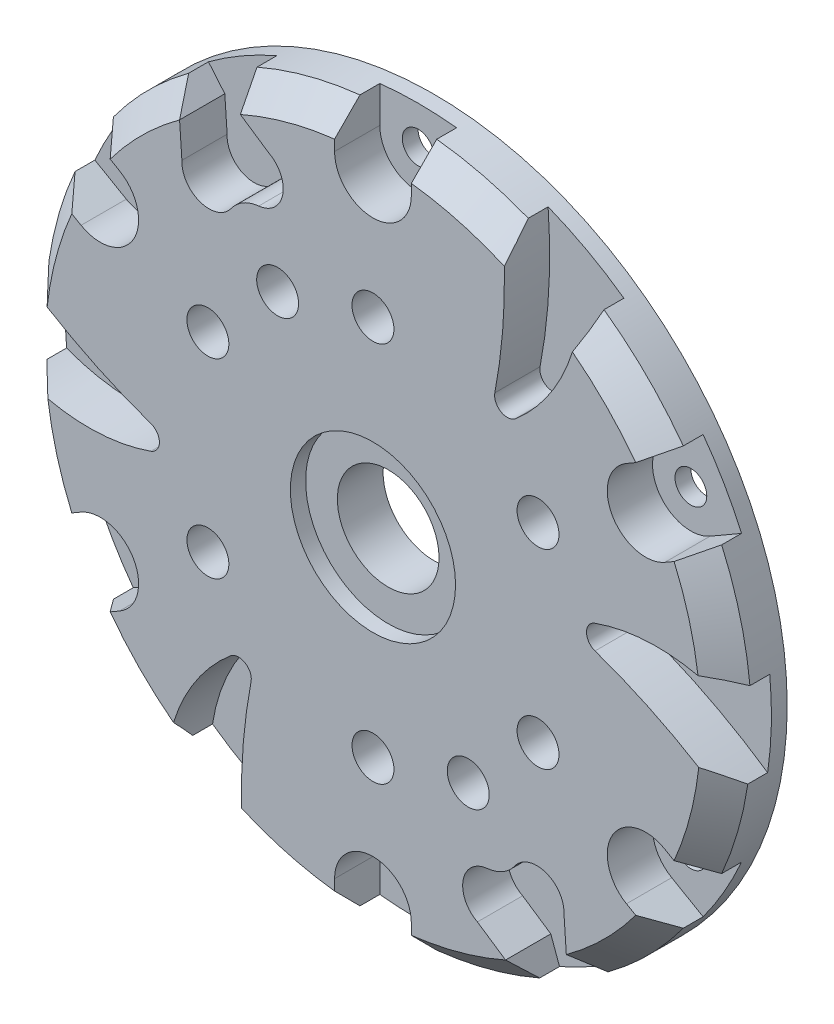
SolidWorks part; units mm, degrees
ref_plane "Front Plane" through (0, 0, 0) normal (0, 0, 1) x (1, 0, 0)
ref_plane "Top Plane" through (0, 0, 0) normal (0, 1, 0) x (1, 0, 0)
ref_plane "Right Plane" through (0, 0, 0) normal (1, 0, 0) x (0, 0, -1)
sketch "Sketch1" plane through (0, 0, 0) normal (0, 0, 1) x (1, 0, 0)
  circle A0 centre (0, 0) radius 27.8
  dimension "D1" = 55.6
extrude "Boss-Extrude1" add sketch "Sketch1" along normal blind 4.8
chamfer "Chamfer1" distance 2 angle 45 1 edges at (27.8, 0, 4.8)
sketch "Sketch2" plane through (0, 0, 4.8) normal (0, 0, 1) x (1, 0, 0)
  line L0 (0, 0) -> (0, 27.8) construction
  line L1 (-3.02, 24.78) -> (-3.02, 27.6355)
  line L2 (3.02, 24.78) -> (3.02, 27.6355)
  line L3 (19.9501, 15.0054) -> (22.423, 16.4331)
  line L4 (22.9701, 9.7746) -> (25.443, 11.2023)
  line L5 (0, 0) -> (24.0755, 13.9) construction
  line L6 (22.9701, -9.7746) -> (25.443, -11.2023)
  line L7 (19.9501, -15.0054) -> (22.423, -16.4331)
  line L8 (0, 0) -> (24.0755, -13.9) construction
  line L9 (3.02, -24.78) -> (3.02, -27.6355)
  line L10 (-3.02, -24.78) -> (-3.02, -27.6355)
  line L11 (0, 0) -> (0, -27.8) construction
  line L12 (-19.9501, -15.0054) -> (-22.423, -16.4331)
  line L13 (-22.9701, -9.7746) -> (-25.443, -11.2023)
  line L14 (0, 0) -> (-24.0755, -13.9) construction
  line L15 (-22.9701, 9.7746) -> (-25.443, 11.2023)
  line L16 (-19.9501, 15.0054) -> (-22.423, 16.4331)
  line L17 (0, 0) -> (-24.0755, 13.9) construction
  line L20 (0, 0) -> (-12.9, 22.3435) construction
  line L21 (-9.1968, 20.2054) -> (-7.9168, 17.9884) construction
  line L22 (-12.9, 18.0674) -> (-11.62, 15.8503) construction
  line L23 (-8.2184, 22.1064) -> (-10.4348, 23.5957)
  line L24 (-10.4348, 23.5957) -> (-11.3266, 26.0379)
  line L25 (-15.2171, 20.8346) -> (-16.8862, 22.8281)
  line L26 (-15.0356, 18.1705) -> (-15.2171, 20.8346)
  line L27 (8.2184, -22.1064) -> (10.4348, -23.5957)
  line L28 (15.0356, -18.1705) -> (15.2171, -20.8346)
  line L29 (15.2171, -20.8346) -> (16.8862, -22.8281)
  line L30 (10.4348, -23.5957) -> (11.3266, -26.0379)
  line L31 (3, -5.1962) -> (-21.0755, -19.0962) construction
  line L32 (3, -5.1962) -> (27.0755, 8.7038) construction
  line L33 (-3, 5.1962) -> (-27.0755, -8.7038) construction
  line L34 (-3, 5.1962) -> (21.0755, 19.0962) construction
  arc A0 (-3.02, 24.78) -> (3.02, 24.78) centre (0, 24.78) ccw
  circle A1 centre (0, 0) radius 27.8 construction
  arc A2 (19.9501, 15.0054) -> (22.9701, 9.7746) centre (21.4601, 12.39) ccw
  arc A3 (22.9701, -9.7746) -> (19.9501, -15.0054) centre (21.4601, -12.39) ccw
  arc A4 (3.02, -24.78) -> (-3.02, -24.78) centre (0, -24.78) ccw
  arc A5 (-19.9501, -15.0054) -> (-22.9701, -9.7746) centre (-21.4601, -12.39) ccw
  arc A6 (-22.9701, 9.7746) -> (-19.9501, 15.0054) centre (-21.4601, 12.39) ccw
  arc A7 (-11.0484, 19.1364) -> (-11.1022, 19.2245) centre (-12.9, 18.0674) ccw
  arc A8 (-8.9908, 18.0773) -> (-8.2184, 22.1064) centre (-9.1968, 20.2054) ccw
  circle A9 centre (0, 0) radius 25.8 construction
  circle A10 centre (0, 0) radius 22.2 construction
  arc A11 (-11.16, 16.8249) -> (-8.9908, 18.0773) centre (-8.6994, 15.0678) cw
  circle A12 centre (0, 0) radius 28.3948 construction
  arc A13 (-15.0356, 18.1705) -> (-11.16, 16.8249) centre (-12.9, 18.0674) ccw
  arc A14 (-11.0978, 19.227) -> (-11.0484, 19.1364) centre (-9.1968, 20.2054) ccw
  arc A16 (8.2184, -22.1064) -> (8.9908, -18.0773) centre (9.1968, -20.2054) cw
  arc A17 (8.9908, -18.0773) -> (11.16, -16.8249) centre (8.6994, -15.0678) ccw
  arc A18 (11.16, -16.8249) -> (15.0356, -18.1705) centre (12.9, -18.0674) cw
  arc A19 (11.3266, -26.0379) -> (16.8862, -22.8281) centre (0, 0) ccw
  arc A20 (-22.423, 16.4331) -> (-25.443, 11.2023) centre (0, 0) ccw
  arc A21 (3.02, 27.6355) -> (-3.02, 27.6355) centre (0, 0) ccw
  arc A22 (25.443, 11.2023) -> (22.423, 16.4331) centre (0, 0) ccw
  arc A23 (22.423, -16.4331) -> (25.443, -11.2023) centre (0, 0) ccw
  arc A24 (-3.02, -27.6355) -> (3.02, -27.6355) centre (0, 0) ccw
  arc A25 (-25.443, -11.2023) -> (-22.423, -16.4331) centre (0, 0) ccw
  arc A26 (11.2246, 13.6916) -> (16.2719, 23.27) centre (1.7214, 24.8184) ccw
  circle A27 centre (0, 0) radius 15 construction
  arc A28 (9.5929, 14.6399) -> (10.1684, 26.5117) centre (-32.0867, 22.6102) ccw
  arc A29 (11.2246, 13.6916) -> (9.5929, 14.6399) centre (10.5751, 14.4521) cw
  arc A30 (17.4696, 2.8749) -> (28.2883, 2.4569) centre (22.3541, -10.9184) cw
  arc A31 (17.4696, 2.8749) -> (17.475, 0.9878) centre (17.8034, 1.9323) ccw
  arc A32 (17.475, 0.9878) -> (28.044, -4.4497) centre (3.5377, -39.093) cw
  arc A33 (-17.4696, -2.8749) -> (-28.2883, -2.4569) centre (-22.3541, 10.9184) cw
  arc A34 (-9.5929, -14.6399) -> (-10.1684, -26.5117) centre (32.0867, -22.6102) ccw
  arc A35 (-11.2246, -13.6916) -> (-9.5929, -14.6399) centre (-10.5751, -14.4521) cw
  arc A36 (-11.2246, -13.6916) -> (-16.2719, -23.27) centre (-1.7214, -24.8184) ccw
  arc A37 (-17.4696, -2.8749) -> (-17.475, -0.9878) centre (-17.8034, -1.9323) ccw
  arc A38 (-17.475, -0.9878) -> (-28.044, 4.4497) centre (-3.5377, 39.093) cw
  arc A39 (-11.3266, 26.0379) -> (-16.8862, 22.8281) centre (0, 0) ccw
  arc A40 (16.2719, 23.27) -> (10.1684, 26.5117) centre (0, 0) ccw
  arc A41 (28.044, -4.4497) -> (21.0354, 19.073) centre (0, 0) ccw
  arc A42 (-16.2719, -23.27) -> (-10.1684, -26.5117) centre (0, 0) ccw
  arc A43 (-28.044, 4.4497) -> (-21.0354, -19.073) centre (0, 0) ccw
  point P88 (9.0378, 12.1462)
  point P91 (9.0378, 12.1462)
  dimension "D1" = 6.04
  dimension "D4" = 30
  dimension "D5" = 44.4
  dimension "D6" = 2.138
  dimension "D7" = 3.0236
  dimension "D11" = 30
  dimension "D12" = 1
  dimension "D8" = 5.5221
  dimension "D9" = 6.4197
  dimension "D10" = 7.8718
extrude "Cut-Extrude1" cut sketch "Sketch2" against normal blind 3.56
hole_wizard "M4x0.7 Tapped Hole1" positions "Sketch6" profile "Sketch3" tap size "M4x0.7" standard "ANSI Metric"
sketch "Sketch6" plane through (0, 0, 4.8) normal (0, 0, 1) x (1, 0, 0)
  line L0 (0.001, 0) -> (0, 15) construction
  line L1 (0.001, 0) -> (7.5001, 12.9909) construction
  circle A0 centre (0, 0) radius 15 construction
  point P0 (0, 15)
  point P26 (7.5001, 12.9909) [skipped]
  point P27 (12.9909, 7.5009)
  point P28 (15.001, 0.001) [skipped]
  point P29 (12.9919, -7.4991)
  point P30 (7.5019, -12.9899)
  point P31 (0.002, -15)
  point P32 (-7.4981, -12.9909) [skipped]
  point P33 (-12.9889, -7.5009)
  point P34 (-14.999, -0.001) [skipped]
  point P35 (-12.9899, 7.4991)
  point P36 (-7.4999, 12.9899)
  dimension "D1" = 30
  dimension "D3" = 30
  dimension "D2" = 12
sketch "Sketch3" plane through (0, 15, 4.8) normal (1, 0, 0) x (0, -1, 0)
  line L0 (0, 0) -> (0, 4.8)
  line L1 (0, 4.8) -> (1.65, 4.8)
  line L2 (1.65, 4.8) -> (1.65, 0)
  line L5 (1.65, 0) -> (0, 0)
  line L11 (0, -6.35) -> (0, 107.95) construction
  dimension "Thru Tap Drill Dia." = 3.3
  dimension "Thru Tap Drill Depth" = 4.8
cosmetic thread "Hole Thread1" parameters "D2"=4
cosmetic thread "Hole Thread2" parameters "D2"=4
cosmetic thread "Hole Thread3" parameters "D2"=4
cosmetic thread "Hole Thread4" parameters "D2"=4
cosmetic thread "Hole Thread5" parameters "D2"=4
cosmetic thread "Hole Thread6" parameters "D2"=4
cosmetic thread "Hole Thread7" parameters "D2"=4
cosmetic thread "Hole Thread8" parameters "D2"=4
sketch "Sketch7" plane through (0, 0, 4.8) normal (0, 0, 1) x (1, 0, 0)
  circle A0 centre (0, 0) radius 4
  dimension "D1" = 8
extrude "Cut-Extrude2" cut sketch "Sketch7" against normal through all
sketch "Sketch8" plane through (0, 0, 4.8) normal (0, 0, 1) x (1, 0, 0)
  circle A0 centre (0, 0) radius 6.5
  dimension "D1" = 13
extrude "Cut-Extrude3" cut sketch "Sketch8" against normal blind 1.2
hole_wizard "M3x0.5 Tapped Hole2" positions "Sketch10" profile "Sketch9" tap size "M3x0.5" standard "ANSI Metric" end condition through all
sketch "Sketch10" plane through (0, 0, 4.8) normal (0, 0, 1) x (1, 0, 0)
  arc A0 (-3.02, 24.78) -> (3.02, 24.78) centre (0, 24.78) ccw construction
  point P0 (0, 24.78)
  point P12 (21.4601, 12.39)
  point P13 (21.4601, -12.39)
  point P14 (0, -24.78)
  point P15 (-21.4601, -12.39)
  point P16 (-21.4601, 12.39)
  point P17 (0, 0)
  dimension "D1" = 0
  dimension "D2" = 6
sketch "Sketch9" plane through (0, 24.78, 4.8) normal (1, 0, 0) x (0, -1, 0)
  line L0 (0, 0) -> (0, 4.8)
  line L1 (0, 4.8) -> (1.25, 4.8)
  line L2 (1.25, 4.8) -> (1.25, 0)
  line L5 (1.25, 0) -> (0, 0)
  line L11 (0, -6.35) -> (0, 107.95) construction
  dimension "Thru Tap Drill Dia." = 2.5
  dimension "Thru Tap Drill Depth" = 4.8
cosmetic thread "Hole Thread9" parameters "D2"=3
cosmetic thread "Hole Thread10" parameters "D2"=3
cosmetic thread "Hole Thread11" parameters "D2"=3
cosmetic thread "Hole Thread12" parameters "D2"=3
cosmetic thread "Hole Thread13" parameters "D2"=3
cosmetic thread "Hole Thread14" parameters "D2"=3
